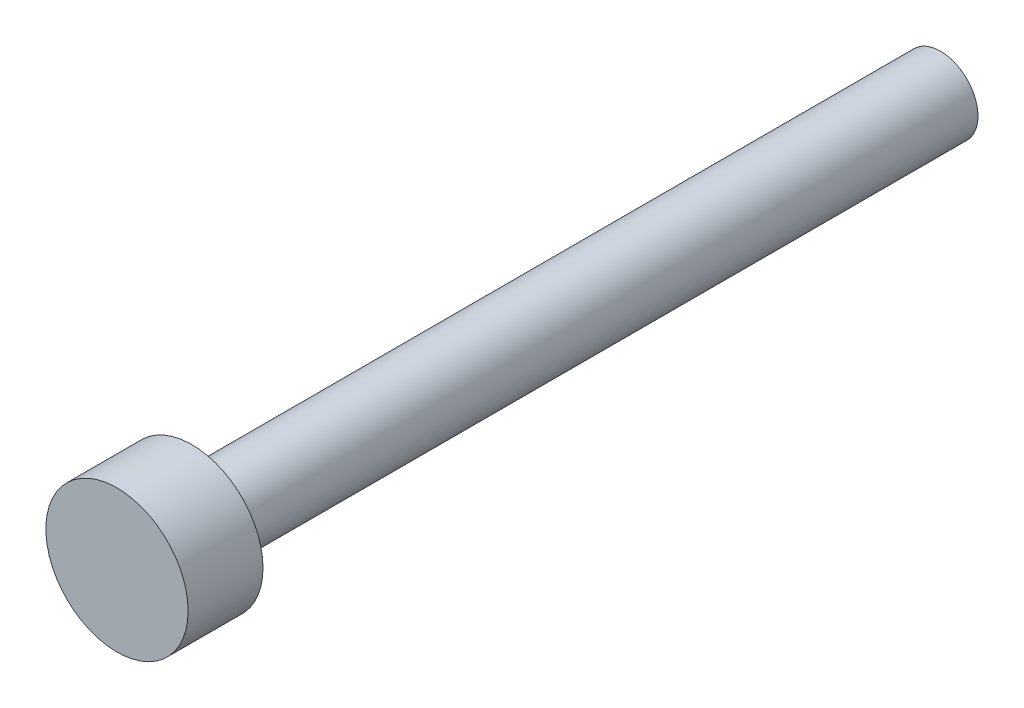
SolidWorks part; units mm, degrees
ref_plane "Front Plane" through (0, 0, 0) normal (0, 0, 1) x (1, 0, 0)
ref_plane "Top Plane" through (0, 0, 0) normal (0, 1, 0) x (1, 0, 0)
ref_plane "Right Plane" through (0, 0, 0) normal (1, 0, 0) x (0, 0, -1)
sketch "Shank_nominal_thread_envelope_profile" plane through (0, 0, 0) normal (0, 0, 1) x (1, 0, 0)
  circle A0 centre (0, 0) radius 1
  dimension "D1" = 2
extrude "Shank_nominal_thread_envelope" add sketch "Shank_nominal_thread_envelope_profile" along normal blind 20 from offset 20
sketch "Socket_head_envelope_profile" plane through (0, 0, 0) normal (0, 0, 1) x (1, 0, 0)
  circle A0 centre (0, 0) radius 1.9
  dimension "D1" = 3.8
extrude "Socket_head_envelope" add sketch "Socket_head_envelope_profile" along normal blind 2
